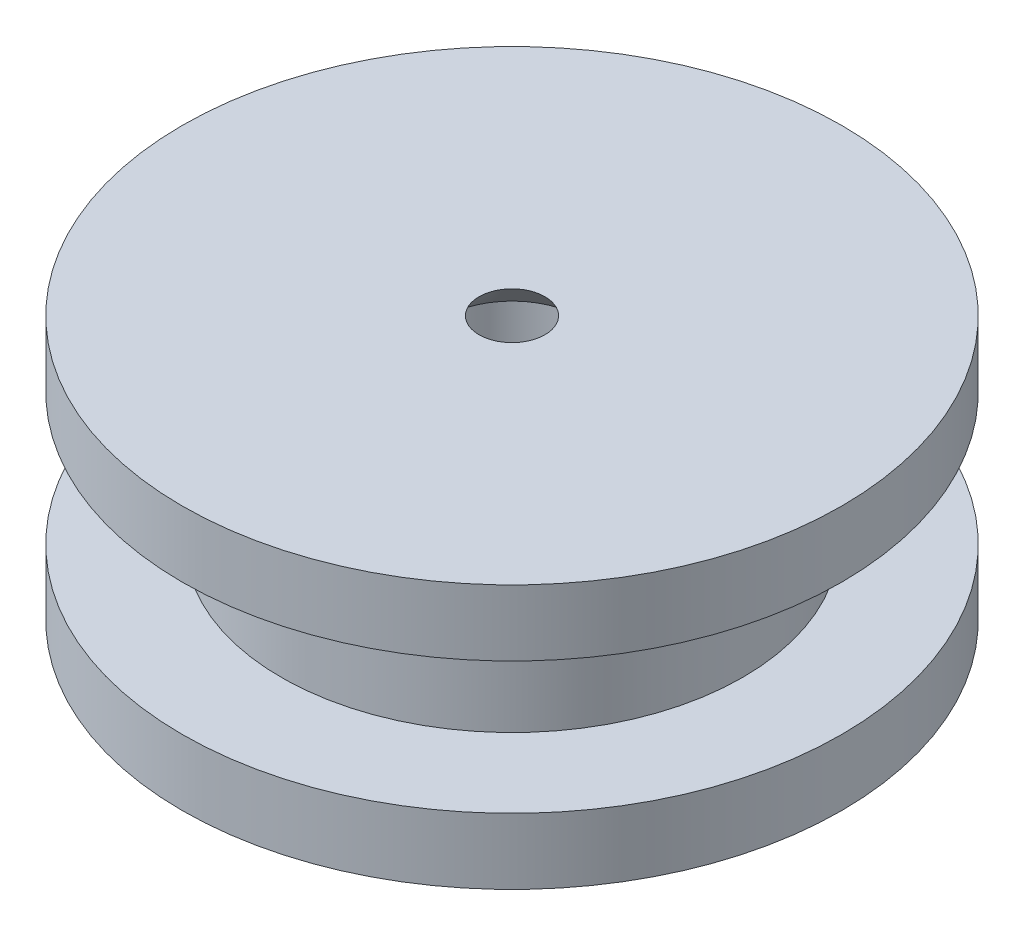
SolidWorks part; units mm, degrees
ref_plane "Front Plane" through (0, 0, 0) normal (0, 0, 1) x (1, 0, 0)
ref_plane "Top Plane" through (0, 0, 0) normal (0, 1, 0) x (1, 0, 0)
ref_plane "Right Plane" through (0, 0, 0) normal (1, 0, 0) x (0, 0, -1)
sketch "Sketch2" plane through (0, 0, 0) normal (0, 0, 1) x (1, 0, 0)
  line L0 (-5, 2) -> (-5, 1)
  line L1 (-5, 1) -> (-3.5, 1)
  line L2 (-3.5, 1) -> (-3.5, -1)
  line L3 (-3.5, -1) -> (-5, -1)
  line L4 (-5, -1) -> (-5, -2)
  line L5 (-5, -2) -> (-1.05, -2)
  line L6 (0, -2) -> (0, 2) construction
  line L7 (0, 2) -> (-5, 2)
  line L8 (-1.05, -2) -> (-1.05, 1.45)
  line L9 (-1.05, 1.45) -> (-0.5, 2)
  point P2 (0, 0)
  point P10 (-3.5, -0.6951)
  point P13 (0, 0)
  dimension "D1" = 4
  dimension "D2" = 10
  dimension "D3" = 7
  dimension "D4" = 1.5
  dimension "D5" = 1
  dimension "D6" = 2.1
  dimension "D7" = 1
  dimension "D8" = 45
revolve "Revolve1" add sketch "Sketch2" angle 360 about L6
